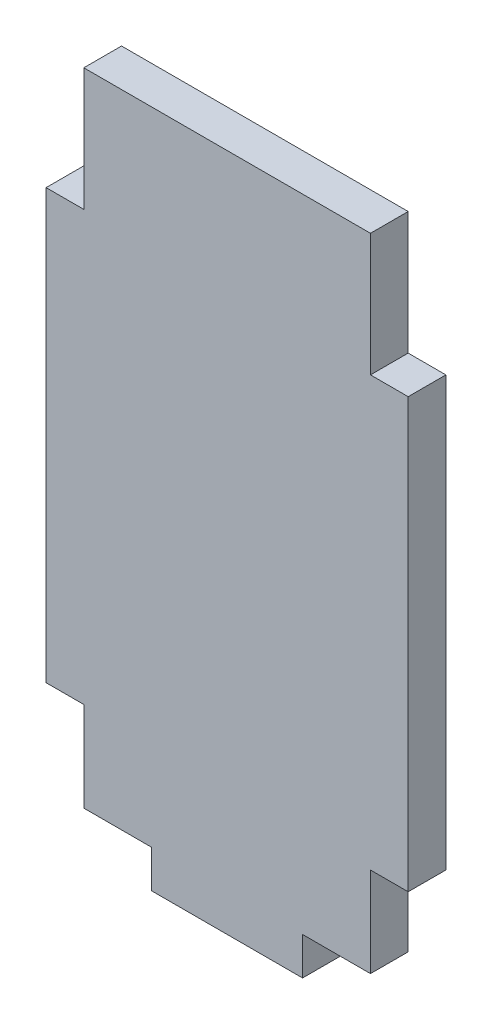
SolidWorks part; units mm, degrees
ref_plane "Ebene vorne" through (0, 0, 0) normal (0, 0, 1) x (1, 0, 0)
ref_plane "Ebene oben" through (0, 0, 0) normal (0, 1, 0) x (1, 0, 0)
ref_plane "Ebene rechts" through (0, 0, 0) normal (1, 0, 0) x (0, 0, -1)
sketch "Skizze1" plane through (0, 0, 0) normal (0, 0, 1) x (1, 0, 0)
  line L1 (-38, 13.6432) -> (0, 13.6432)
  line L2 (-38, 13.6432) -> (-38, -71.3568)
  line L3 (-38, -71.3568) -> (0, -71.3568)
  line L4 (0, 13.6432) -> (0, -71.3568)
  line L5 (-38, 13.6432) -> (0, -71.3568) construction
  line L6 (-38, -71.3568) -> (0, 13.6432) construction
  line L8 (5, -2.6147) -> (5, -59.4568)
  line L9 (-9, -76.3568) -> (-29, -76.3568)
  line L10 (-43, -2.6147) -> (-43, -59.4568)
  line L11 (0, 8.2266) -> (-38, -65.9401) construction
  line L12 (0, -70.9401) -> (-38, 13.2266) construction
  line L15 (-29, -71.3568) -> (-29, -76.3568)
  line L16 (-9, -71.3568) -> (-9, -76.3568)
  line L31 (5, -2.6147) -> (0, -2.6147)
  line L32 (-38, -2.6147) -> (-43, -2.6147)
  line L33 (5, -59.4568) -> (0, -59.4568)
  line L34 (-38, -59.4568) -> (-43, -59.4568)
  point P0 (-19, -28.8568)
  point P5 (-19, -28.8568)
  dimension "D1" = 11.9
  dimension "D2" = 38
  dimension "D3" = 85
extrude "Aufsatz-Linear austragen1" add sketch "Skizze1" along normal blind 5 contours L4 L1 L2 L3 | L33 L8 L31 L4 | L16 L3 L15 L9 | L34 L2 L32 L10
